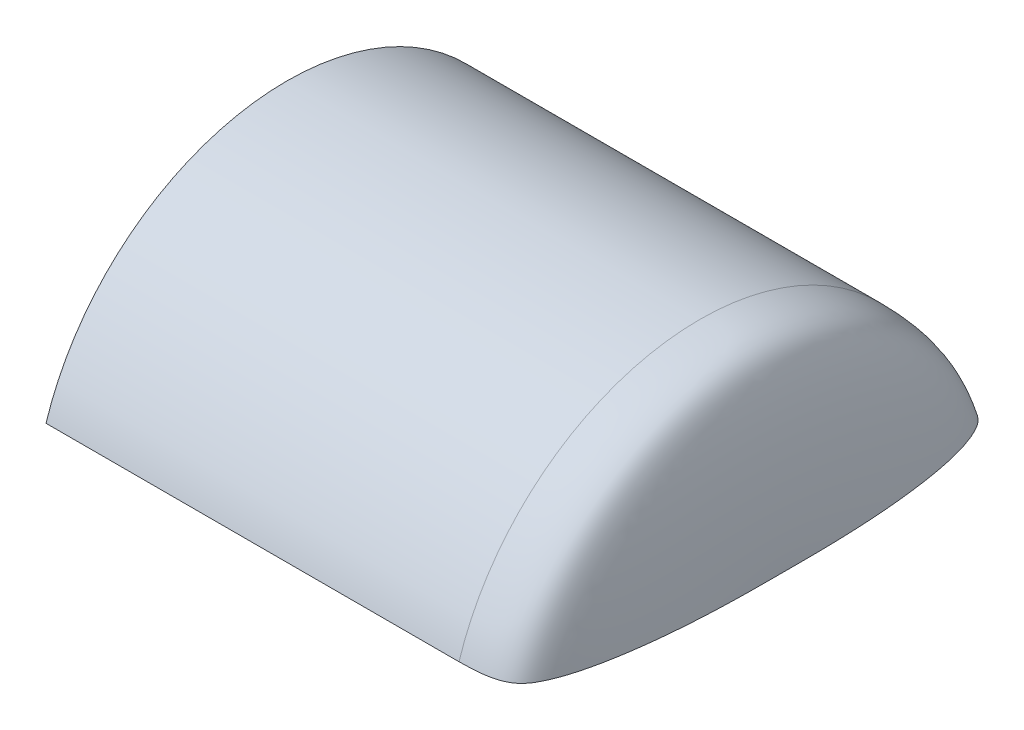
SolidWorks part; units mm, degrees
ref_plane "Plano frontal" through (0, 0, 0) normal (0, 0, 1) x (1, 0, 0)
ref_plane "Plano superior" through (0, 0, 0) normal (0, 1, 0) x (1, 0, 0)
ref_plane "Plano direito" through (0, 0, 0) normal (1, 0, 0) x (0, 0, -1)
sketch "Esboço1" plane through (0, 0, 0) normal (0, 0, 1) x (1, 0, 0)
  line L1 (-27, -15) -> (27, -15) construction
  line L2 (-27, -15) -> (-27, 15) construction
  line L3 (-27, 15) -> (27, 15) construction
  line L4 (27, -15) -> (27, 15) construction
  line L5 (-27, -15) -> (27, 15) construction
  line L6 (-27, 15) -> (27, -15) construction
  point P0 (0, 0)
  dimension "D1" = 54
  dimension "D2" = 30
ref_axis "Eixo1" through (-27, -15, 0) along (1, 0, 0)
sketch "Esboço2" plane through (0, 0, 0) normal (0, 0, 1) x (1, 0, 0)
  line L0 (-27, 18) -> (-27, 15)
  line L1 (38, -11.2715) -> (38, 1.2715) construction
  line L2 (-27, 15) -> (27, 15)
  line L3 (27, -15) -> (27, 15) construction
  line L4 (-27, 18) -> (26.8865, 18)
  line L5 (-27, 15) -> (27, 15) construction
  line L6 (33.7202, 18) -> (20.0527, 18) construction
  line L7 (35, -5) -> (38, -5)
  line L8 (28.9233, 15) -> (23.5363, 15) construction
  line L9 (35, -5.3845) -> (35, -2.8376) construction
  spline S0 degree 3 poles (27, 15) (34.6667, 15) (35, -2.1849) (35, -5) knots 0 0 0 0 1 1 1 1
  spline S1 degree 3 poles (26.8865, 18) (32.0984, 18) (37.0755, 14.3644) (38, -2) (38, -5) knots 0 0 0 0 0.277641 1 1 1 1
  point P10 (27, -5)
  dimension "D5" = 23
  dimension "D6" = 15.6357
  dimension "D7" = 9
  dimension "D1" = 3
  dimension "D3" = 20
  dimension "D4" = 3
revolve "Revolução1" add sketch "Esboço2" angle 360 about axis through (-27, -15, 0) along (1, 0, 0)
ref_plane "Plano1" through (38, 0, 0) normal (1, 0, 0) x (0, 0, -1)
sketch "Esboço3" plane through (38, 0, 0) normal (1, 0, 0) x (0, 0, -1)
  line L0 (-31.4483, -5) -> (31.4483, -5)
  arc A0 (31.4483, -5) -> (-31.4483, -5) centre (0, -15) ccw
  circle A1 centre (0, -15) radius 10 construction
extrude "Corte-extrusão1" cut sketch "Esboço3" against normal through all flip side to cut
sketch "Esboço5" plane through (0, 0, 0) normal (0, 0, 1) x (1, 0, 0)
  line L0 (27, -15) -> (27, 15) construction
  line L1 (27, 5) -> (37.208, 5) construction
  line L2 (10.8551, -5) -> (-7.6449, -5)
  line L3 (30, 5) -> (34.208, 5) construction
  line L6 (26.9526, -5) -> (-27, -5) construction
  line L7 (-27, 17.9999) -> (-27, -5) construction
  line L8 (-27, -5) -> (26.9526, -5) construction
  line L12 (-27, 18) -> (-27, 12)
  line L13 (-27, -15) -> (-27, 15) construction
  line L14 (26.127, 5) -> (13.8551, 5)
  line L15 (12.3551, 3.5) -> (12.3551, -3.5)
  line L16 (10.8551, -5) -> (-7.6449, -5)
  line L17 (-15.0292, 12) -> (-38.9708, 12) construction
  line L18 (2.785, -5) -> (-18.0747, -5) construction
  line L19 (-27, 17.9999) -> (-27, 12)
  line L21 (-7.6449, -5) -> (10.8551, -5)
  line L23 (30, 2) -> (34.208, 2)
  line L25 (-27, 17.9999) -> (26.9526, 17.9999)
  arc A0 (27.0953, 4.25) -> (30, 2) centre (30, 5) ccw
  arc A1 (34.208, 2) -> (37.208, 5) centre (34.208, 5) ccw
  arc A2 (13.8551, 5) -> (12.3551, 3.5) centre (13.8551, 3.5) ccw
  arc A3 (12.3551, -3.5) -> (10.8551, -5) centre (10.8551, -3.5) cw
  arc A4 (26.127, 5) -> (27.0953, 4.25) centre (26.127, 4) cw
  spline S2 degree 3 poles (-1966.0192, -147.6482) (-3.713, -17.8588) (78.3469, 118.573) (-0.2134, -249.4672) (134.8695, 1992.4875) knots -1.991716 -1.991716 -1.991716 -1.991716 0.27679 4.311145 4.311145 4.311145 4.311145 only from (26.9526, 17.9999) to (38, -5)
  spline S3 degree 3 poles (26.9526, 17.9999) (32.1101, 17.9914) (35.1582, 15.7536) (36.6834, 8.7325) (37.208, 5) knots 0 0 0 0 0.27679 0.613729 0.613729 0.613729 0.613729
  spline S4 degree 3 poles (-27, 12) (-18.6667, 12) (-15.9782, -5) (-7.6449, -5) knots 0 0 0 0 1 1 1 1
  point P9 (32.104, 5)
  dimension "D6" = 25
  dimension "D7" = 25
  dimension "D4" = 1
  dimension "D2" = 3
  dimension "D3" = 6
